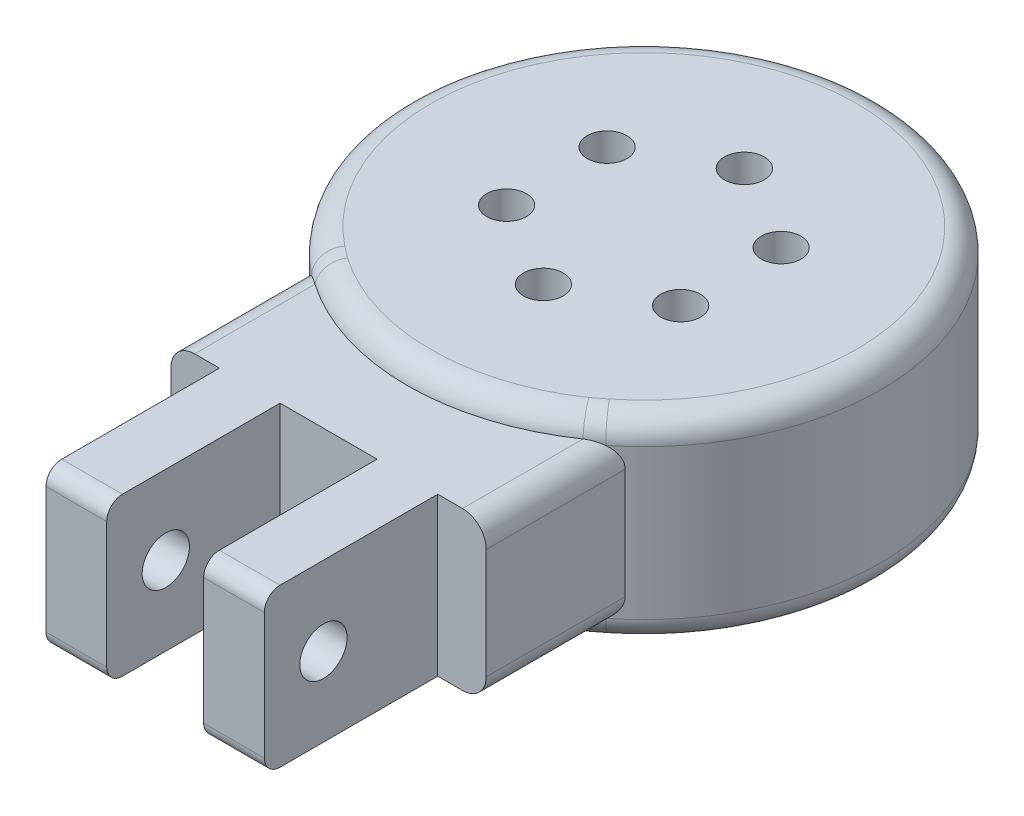
SolidWorks part; units mm, degrees
ref_plane "Front Plane" through (0, 0, 0) normal (0, 0, 1) x (1, 0, 0)
ref_plane "Top Plane" through (0, 0, 0) normal (0, 1, 0) x (1, 0, 0)
ref_plane "Right Plane" through (0, 0, 0) normal (1, 0, 0) x (0, 0, -1)
sketch "Sketch1" plane through (0, 0, 0) normal (0, 1, 0) x (1, 0, 0)
  line L1 (20, 10) -> (-20, 10)
  line L2 (20, 10) -> (20, -10)
  line L3 (20, -10) -> (-20, -10)
  line L4 (-20, 10) -> (-20, -10)
  line L5 (20, 10) -> (-20, -10) construction
  line L6 (20, -10) -> (-20, 10) construction
  point P0 (0, 0)
  dimension "D1" = 40
  dimension "D2" = 20
extrude "Boss-Extrude1" add sketch "Sketch1" along normal mid plane 20
fillet "Fillet1" radius 3 4 edges at (-20, 10, 0) (-20, -10, 0) (20, 10, 0) (20, -10, 0)
sketch "Sketch3" plane through (0, 0, 0) normal (0, 1, 0) x (1, 0, 0)
  line L0 (0, 0) -> (0, 30) construction
  circle A0 centre (0, 30) radius 30
  dimension "35" = 30
extrude "Boss-Extrude2" add sketch "Sketch3" along normal mid plane 25
fillet "Fillet2" radius 3 2 edges at (0, -12.5, 0) (0, 12.5, 0)
sketch "Sketch4" plane through (0, 0, 10) normal (0, 0, 1) x (1, 0, 0)
  line L9 (15.6, 5.6) -> (-15.6, 5.6)
  line L10 (-15.6, 5.6) -> (-15.6, -5.6)
  line L11 (-15.6, -5.6) -> (15.6, -5.6)
  line L12 (15.6, -5.6) -> (15.6, 5.6)
  line L13 (15.6, 5.6) -> (-15.6, 5.6)
  line L14 (-15.6, 5.6) -> (-15.6, -5.6)
  line L15 (-15.6, -5.6) -> (15.6, -5.6)
  line L16 (15.6, -5.6) -> (15.6, 5.6)
  dimension "D1" = 4.4
sketch "Sketch5" plane through (0, 12.5, 0) normal (0, 1, 0) x (1, 0, 0)
  line L0 (0, 0) -> (0, 182.6104) construction
  line L1 (0, 182.6104) -> (0, 30) construction
  line L2 (0, 30) -> (91.1413, 30) construction
  circle A0 centre (0, 30) radius 12.75
  circle A1 centre (0, 42.75) radius 2.5245
  circle A2 centre (11.0418, 36.375) radius 2.5245
  circle A3 centre (11.0418, 23.625) radius 2.5245
  circle A4 centre (0, 17.25) radius 2.5245
  circle A5 centre (-11.0418, 23.625) radius 2.5245
  circle A6 centre (-11.0418, 36.375) radius 2.5245
  point P21 (0, 30)
  dimension "D2" = 5.049
  dimension "D4" = 25.5
  dimension "D3" = 6
extrude "Cut-Extrude1" cut sketch "Sketch5" against normal through all contours A0 A4 | A6 | A5 | A3 | A2 | A1
sketch "Sketch6" plane through (0, 0, 10) normal (0, 0, 1) x (1, 0, 0)
  line L0 (-17, -10) -> (17, -10) construction
  line L1 (-13.85, 10) -> (-6.15, 10)
  line L2 (-13.85, 10) -> (-13.85, -10)
  line L3 (-13.85, -10) -> (-6.15, -10)
  line L4 (-6.15, 10) -> (-6.15, -10)
  line L5 (-13.85, 10) -> (-6.15, -10) construction
  line L6 (-13.85, -10) -> (-6.15, 10) construction
  line L7 (0, -13.75) -> (0, 13.75) construction
  line L8 (13.85, -10) -> (6.15, -10)
  line L9 (6.15, 10) -> (6.15, -10)
  line L10 (13.85, 10) -> (6.15, 10)
  line L11 (13.85, 10) -> (13.85, -10)
  point P0 (-10, 0)
  dimension "D1" = 10
  dimension "D2" = 7.7
  dimension "D3" = 20
extrude "Boss-Extrude3" add sketch "Sketch6" along normal blind 22
sketch "Sketch7" plane through (-13.85, 0, 0) normal (-1, 0, 0) x (0, 0, 1)
  line L1 (32, 10) -> (32, -10) construction
  circle A0 centre (24.5, 0) radius 3
  dimension "D1" = 6
  dimension "12.4" = 7.5
extrude "Cut-Extrude3" cut sketch "Sketch7" against normal through all both and the other way through all
fillet "Fillet3" radius 2 4 edges at (10, -10, 32) (10, 10, 32) (-10, -10, 32) (-10, 10, 32)
